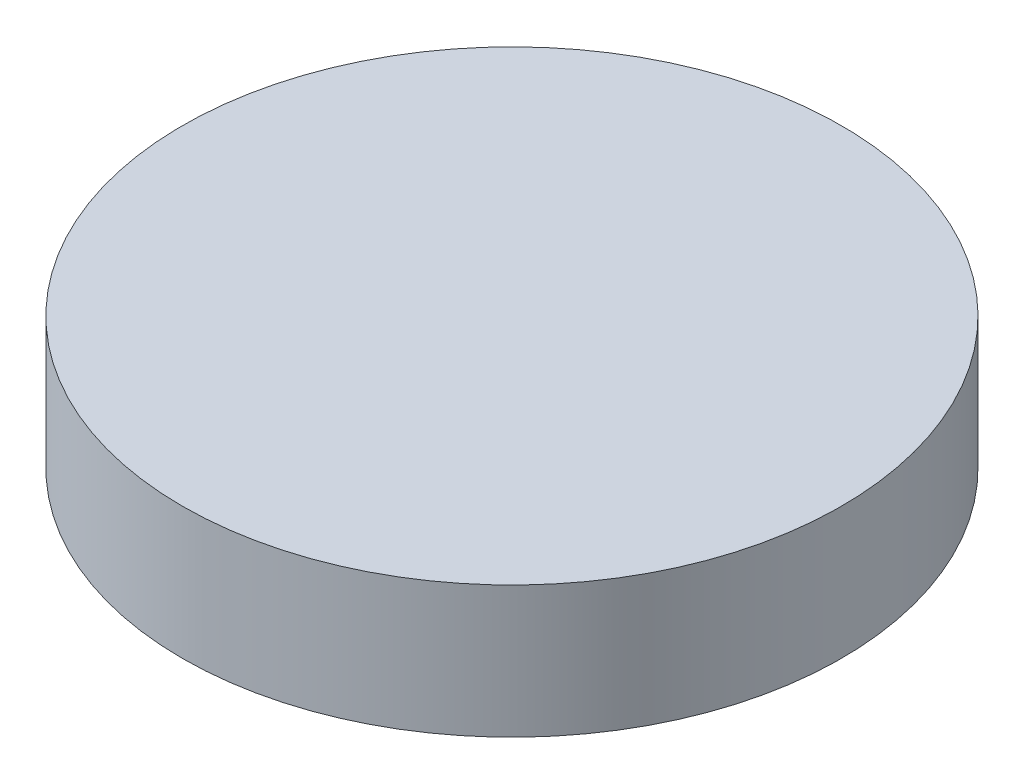
SolidWorks part; units mm, degrees
material "BUTYL"
ref_plane "前视基准面" through (0, 0, 0) normal (0, 0, 1) x (1, 0, 0)
ref_plane "上视基准面" through (0, 0, 0) normal (0, 1, 0) x (1, 0, 0)
ref_plane "右视基准面" through (0, 0, 0) normal (1, 0, 0) x (0, 0, -1)
other "Configuration Table"
sketch "草图1" plane through (0, 0, 0) normal (0, 1, 0) x (1, 0, 0)
  circle A0 centre (0, 0) radius 20
  dimension "D1" = 40
extrude "凸台-拉伸1" add sketch "草图1" along normal blind 8
